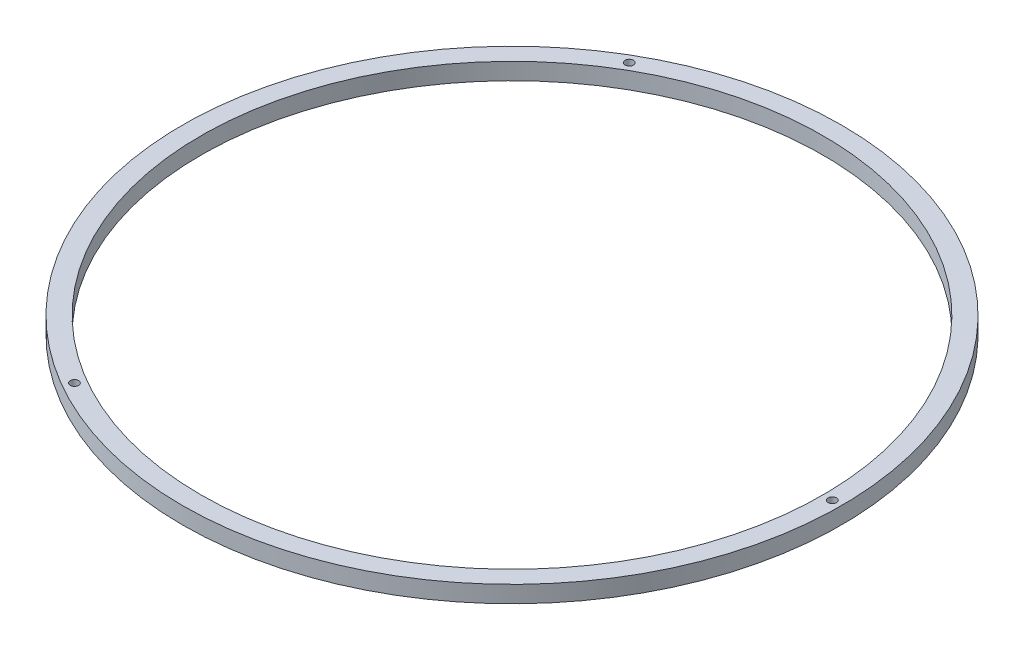
SolidWorks part; units mm, degrees
ref_plane "前视基准面" through (0, 0, 0) normal (0, 0, 1) x (1, 0, 0)
ref_plane "上视基准面" through (0, 0, 0) normal (0, 1, 0) x (1, 0, 0)
ref_plane "右视基准面" through (0, 0, 0) normal (1, 0, 0) x (0, 0, -1)
sketch "草图1" plane through (0, 0, 0) normal (0, 1, 0) x (1, 0, 0)
  line L1 (190.5256, 0) -> (-95.2628, 165)
  line L2 (-95.2628, 165) -> (-95.2628, -165)
  line L3 (-95.2628, -165) -> (190.5256, 0)
  circle A0 centre (0, 0) radius 95.2628 construction
  dimension "D1" = 330
sketch "草图2" plane through (0, 0, 0) normal (0, 1, 0) x (1, 0, 0)
  circle A0 centre (0, 0) radius 196
  circle A1 centre (0, 0) radius 185
  circle A2 centre (-95.2628, 165) radius 2.5
  circle A3 centre (190.5256, 0) radius 2.5
  circle A4 centre (-95.2628, -165) radius 2.5
  dimension "D1" = 5
  dimension "D2" = 5
  dimension "D3" = 5
  dimension "D4" = 392
  dimension "380" = 370
extrude "凸台-拉伸1" add sketch "草图2" along normal blind 10
